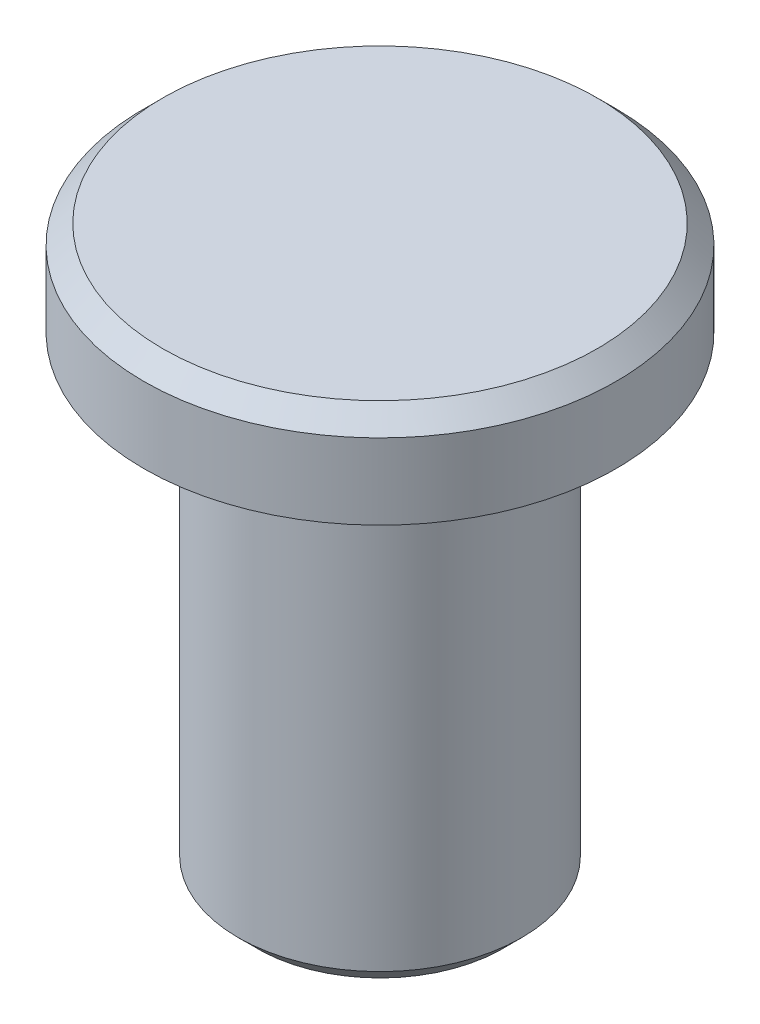
SolidWorks part; units mm, degrees
ref_plane "Front Plane" through (0, 0, 0) normal (0, 0, 1) x (1, 0, 0)
ref_plane "Top Plane" through (0, 0, 0) normal (0, 1, 0) x (1, 0, 0)
ref_plane "Right Plane" through (0, 0, 0) normal (1, 0, 0) x (0, 0, -1)
sketch "Sketch2" plane through (0, 0, 0) normal (0, 0, 1) x (1, 0, 0)
  line L0 (0, 0) -> (0, 6)
  line L1 (0, 6) -> (2.5, 6)
  line L2 (2.5, 6) -> (2.5, 5)
  line L3 (2.5, 5) -> (1.5, 5)
  line L4 (1.5, 5) -> (1.5, 0)
  line L5 (1.5, 0) -> (0, 0)
  dimension "D1" = 6
  dimension "D2" = 2.5
  dimension "D3" = 1
  dimension "D4" = 1.5
  dimension "D5" = 5
revolve "Revolve3" add sketch "Sketch2" angle 360 about L0
chamfer "Chamfer1" distance 0.2 angle 45 2 edges at (0, 0, -1.5) (0, 6, -2.5)
